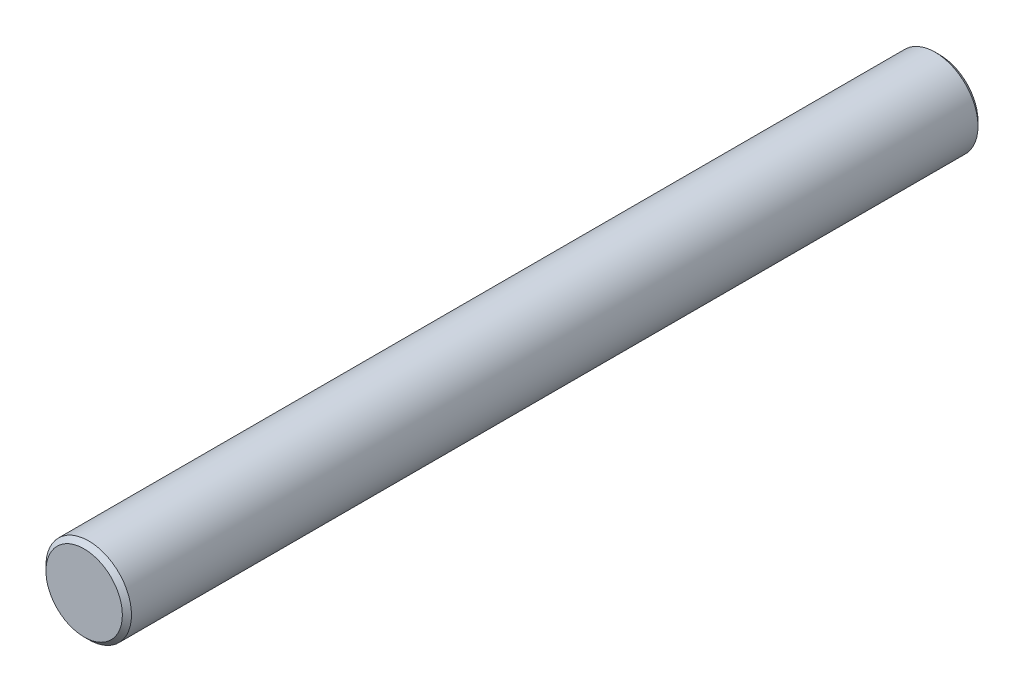
SolidWorks part; units mm, degrees
ref_plane "Front Plane" through (0, 0, 0) normal (0, 0, 1) x (1, 0, 0)
ref_plane "Top Plane" through (0, 0, 0) normal (0, 1, 0) x (1, 0, 0)
ref_plane "Right Plane" through (0, 0, 0) normal (1, 0, 0) x (0, 0, -1)
sketch "Sketch1" plane through (0, 0, 0) normal (0, 0, 1) x (1, 0, 0)
  circle A0 centre (0, 0) radius 4.7625
  dimension "D1" = 9.525
extrude "Boss-Extrude1" add sketch "Sketch1" along normal blind 95.25 contours A0
chamfer "Chamfer1" distance 0.508 angle 45 2 edges at (4.7625, 0, 0) (4.7625, 0, 95.25)
